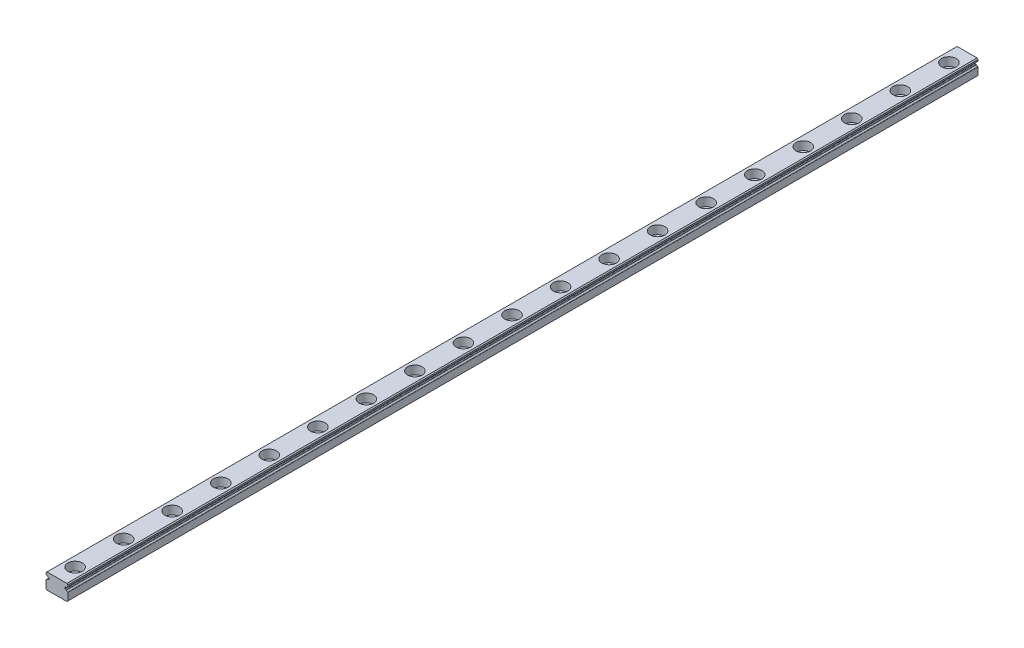
SolidWorks part; units mm, degrees
ref_plane "Front Plane" through (0, 0, 0) normal (0, 0, 1) x (1, 0, 0)
ref_plane "Top Plane" through (0, 0, 0) normal (0, 1, 0) x (1, 0, 0)
ref_plane "Right Plane" through (0, 0, 0) normal (1, 0, 0) x (0, 0, -1)
sketch "Sketch1" plane through (0, 0, 0) normal (0, 0, 1) x (1, 0, 0)
  line L0 (-4.5, 0) -> (4.5, 0) construction
  line L1 (0, -3.25) -> (0, 3.25) construction
  line L2 (0, 3.25) -> (0, -3.25) construction
  line L3 (-3, 3.25) -> (3, 3.25) construction
  line L4 (-1.75, -0.25) -> (1.75, -0.25) construction
  point P0 (0, -0.25)
  point P3 (-4.5, -3.25)
  point P4 (0, 0)
  point P8 (0, 0)
  point P11 (0, 3.25)
  point P15 (0, 3.25)
  point P17 (0, -0.25)
  point P18 (4.5, 3.25)
  point P20 (-4.5, 3.25)
  dimension "Rail Width" = 9
  dimension "Rail Height" = 6.5
  dimension "Mounting Hole Depth" = 3
  dimension "Mounting Hole Counterbore Diameter" = 6
  dimension "Mounting Hole Diameter" = 3.5
sketch "Sketch2" plane through (0, 0, 0) normal (1, 0, 0) x (0, 0, -1)
  line L0 (187.5, 0) -> (-187.5, 0) construction
  line L1 (-9.5, 3.25) -> (9.5, 3.25) construction
  line L3 (0, 3.25) -> (0, 0) construction
  point P0 (-180, 0)
  point P4 (0, 0)
  point P5 (-160, 0)
  point P6 (-170, 0)
  point P9 (-180, 3.25)
  point P10 (0, 3.25)
  point P11 (187.5, 3.25)
  point P13 (-187.5, 3.25)
  point P14 (170, 0)
  point P17 (-187.5, -3.25)
  dimension "Rail Length" = 375
  dimension "Mounting Hole Center to Edge" = 7.5
  dimension "Mounting Hole Center to Center" = 20
  dimension "Number of Mounting Holes" = 19
  dimension "Break Line" = 10
sketch "Sketch3" plane through (0, 0, 0) normal (0, 0, 1) x (1, 0, 0)
  point P0 (0, 3.25)
  line B0 (-4.5, 0.1917) -> (-4.5, -2.85)
  line B1 (-4.5, -2.85) -> (-4.1, -3.25)
  line B2 (-4.1, -3.25) -> (1.4, -3.25)
  line B3 (2.2, -3.25) -> (4.1, -3.25)
  line B4 (4.1, -3.25) -> (4.5, -2.85)
  line B5 (4.5, -2.85) -> (4.5, 0.1917)
  line B6 (3.8235, 0.8135) -> (3.4826, 0.8434)
  line B7 (3.3, 1.0426) -> (3.3, 1.4574)
  line B8 (3.4826, 1.6566) -> (3.8235, 1.6865)
  line B9 (4.5, 2.3083) -> (4.5, 2.85)
  line B10 (4.5, 2.85) -> (4.1, 3.25)
  line B11 (4.1, 3.25) -> (-4.1, 3.25)
  line B12 (-4.1, 3.25) -> (-4.5, 2.85)
  line B13 (-4.5, 2.85) -> (-4.5, 2.3083)
  line B14 (-3.8235, 1.6865) -> (-3.4826, 1.6566)
  line B15 (-3.3, 1.4574) -> (-3.3, 1.0426)
  line B16 (-3.4826, 0.8434) -> (-3.8235, 0.8135)
  arc B17 (2.2, -3.25) -> (1.4, -3.25) centre (1.8, -3.55) ccw
  arc B18 (4.5, 0.1917) -> (4.4087, 0.3297) centre (4.35, 0.1917) ccw
  arc B19 (3.9395, 0.7405) -> (4.4087, 0.3297) centre (4.8, 1.25) ccw
  arc B20 (3.9395, 0.7405) -> (3.8235, 0.8135) centre (3.8104, 0.6641) ccw
  arc B21 (3.3, 1.0426) -> (3.4826, 0.8434) centre (3.5, 1.0426) ccw
  arc B22 (3.4826, 1.6566) -> (3.3, 1.4574) centre (3.5, 1.4574) ccw
  arc B23 (3.8235, 1.6865) -> (3.9395, 1.7595) centre (3.8104, 1.8359) ccw
  arc B24 (4.4087, 2.1703) -> (3.9395, 1.7595) centre (4.8, 1.25) ccw
  arc B25 (4.4087, 2.1703) -> (4.5, 2.3083) centre (4.35, 2.3083) ccw
  arc B26 (-4.5, 2.3083) -> (-4.4087, 2.1703) centre (-4.35, 2.3083) ccw
  arc B27 (-3.9395, 1.7595) -> (-4.4087, 2.1703) centre (-4.8, 1.25) ccw
  arc B28 (-3.9395, 1.7595) -> (-3.8235, 1.6865) centre (-3.8104, 1.8359) ccw
  arc B29 (-3.3, 1.4574) -> (-3.4826, 1.6566) centre (-3.5, 1.4574) ccw
  arc B30 (-3.4826, 0.8434) -> (-3.3, 1.0426) centre (-3.5, 1.0426) ccw
  arc B31 (-3.8235, 0.8135) -> (-3.9395, 0.7405) centre (-3.8104, 0.6641) ccw
  arc B32 (-4.4087, 0.3297) -> (-3.9395, 0.7405) centre (-4.8, 1.25) ccw
  arc B33 (-4.4087, 0.3297) -> (-4.5, 0.1917) centre (-4.35, 0.1917) ccw
sketch_block_instance "9mm Block-1"
sketch_block "9mm Block"
extrude "Boss-Extrude1" add sketch "Sketch3" against normal up to vertex (187.5 mm away) from vertex at 187.5 starting at point (0, 0, 187.5)
ref_plane "Plane1" through (0, 0, 180) normal (0, 0, 1) x (1, 0, 0)
sketch "Sketch4" plane through (0, 0, 180) normal (0, 0, 1) x (1, 0, 0)
  line L0 (0, 3.25) -> (0, -3.25)
  line L1 (0, -3.25) -> (-1.75, -3.25)
  line L3 (-1.75, -3.25) -> (-1.75, -0.25)
  line L4 (-1.75, -0.25) -> (-3, -0.25)
  line L5 (-3, -0.25) -> (-3, 3.25)
  line L6 (-3, 3.25) -> (0, 3.25)
revolve "Cut-Revolve1" cut sketch "Sketch4" angle 360 about L0
sketch "Sketch6" plane through (0, 0, 0) normal (1, 0, 0) x (0, 0, -1)
  line L0 (-177, -0.25) -> (-183, -0.25) construction
  line L5 (-177, -0.25) -> (-183, -0.25)
  line L17 (-181.75, -0.25) -> (-181.75, -3.25) construction
  line L18 (-178.25, -3.25) -> (-178.25, -0.25) construction
  line L32 (-177, -0.25) -> (-177, 3.25) construction
  line L33 (-183, 3.25) -> (-183, -0.25) construction
  line L34 (-181.75, -0.25) -> (-181.75, -3.25)
  line L35 (-178.25, -3.25) -> (-178.25, -0.25)
  line L36 (-177, -0.25) -> (-177, 3.25)
  line L37 (-183, 3.25) -> (-183, -0.25)
  line L38 (0, 3.25) -> (0, -3.25) construction
  line L40 (183, 3.25) -> (183, -0.25)
  line L41 (177, -0.25) -> (177, 3.25)
  line L42 (178.25, -3.25) -> (178.25, -0.25)
  line L43 (181.75, -0.25) -> (181.75, -3.25)
  line L44 (177, -0.25) -> (183, -0.25)
sketch "Sketch7" plane through (0, 0, 0) normal (0, 0, 1) x (1, 0, 0)
  line L0 (3, -0.25) -> (3, 3.25) construction
  line L1 (-3, 3.25) -> (-3, -0.25) construction
  line L2 (3, -0.25) -> (3, 3.25)
  line L3 (-3, 3.25) -> (-3, -0.25)
  line L4 (1.75, -3.0525) -> (1.75, -0.25) construction
  line L11 (1.75, -3.0525) -> (1.75, -0.25)
  line L18 (-1.75, -0.25) -> (-1.75, -3.25) construction
  line L32 (3, -0.25) -> (-3, -0.25) construction
  line L34 (-1.75, -0.25) -> (-1.75, -3.25)
  line L37 (3, -0.25) -> (-3, -0.25)
pattern_linear "LPattern1" count 19 spacing 20 along (0, 0, -1) of "Cut-Revolve1"
equation "\"D3@LPattern1\"=\"Mounting Hole Center to Center@Sketch2\""
equation "\"D1@LPattern1\"=\"Number of Mounting Holes@Sketch2\""
equation "\"Break Line@Sketch2\"=\"Mounting Hole Center to Center@Sketch2\"/2"
